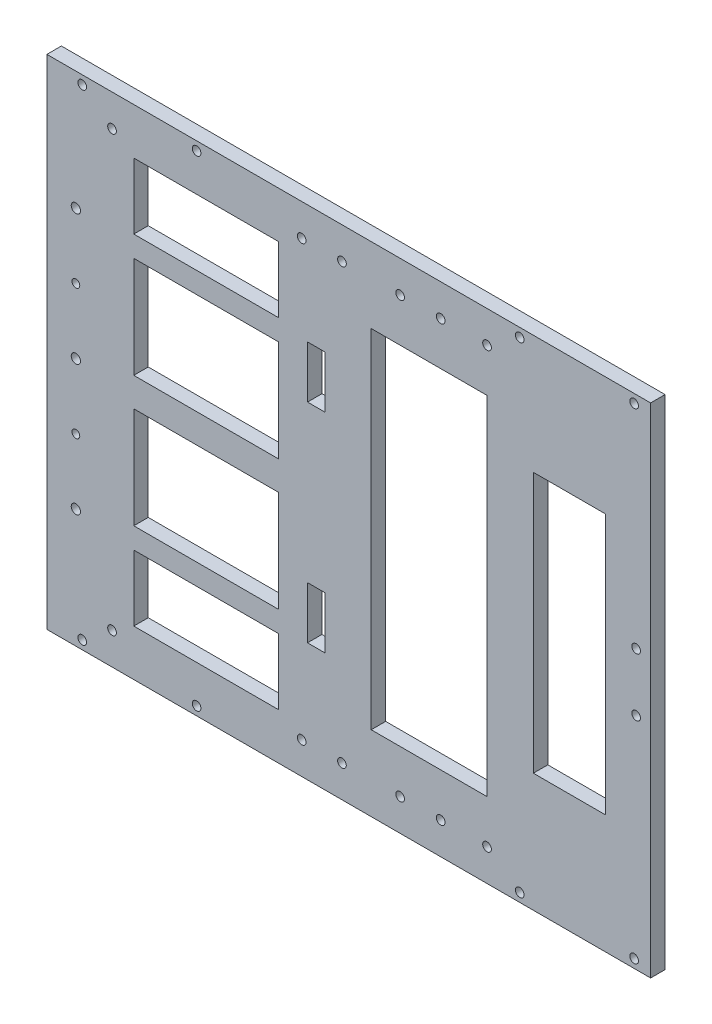
SolidWorks part; units mm, degrees
ref_plane "Front" through (0, 0, 0) normal (0, 0, 1) x (1, 0, 0)
ref_plane "Top" through (0, 0, 0) normal (0, 1, 0) x (1, 0, 0)
ref_plane "Right" through (0, 0, 0) normal (1, 0, 0) x (0, 0, -1)
sketch "草图1" plane through (0, 0, 0) normal (0, 0, 1) x (1, 0, 0)
  line L0 (-105.75, 86) -> (-105.75, 70)
  line L1 (-105.75, 86) -> (105.75, 86)
  line L2 (-105.75, 70) -> (-105.75, -86)
  line L3 (-105.75, -86) -> (105.75, -86)
  line L4 (105.75, 86) -> (105.75, -86)
  line L5 (-105.75, 86) -> (105.75, -86) construction
  line L6 (-105.75, -86) -> (105.75, 86) construction
  line L7 (-129.21, 0) -> (147.9998, 0) construction
  line L8 (-75.75, 70) -> (-25.75, 70)
  line L9 (-25.75, 70) -> (-25.75, 47.25)
  line L10 (-25.75, 47.25) -> (-75.75, 47.25)
  line L11 (-75.75, 47.25) -> (-75.75, 70)
  line L12 (-75.75, 40) -> (-25.75, 40)
  line L13 (-25.75, 40) -> (-25.75, 5)
  line L14 (-25.75, 5) -> (-75.75, 5)
  line L15 (-75.75, 5) -> (-75.75, 40)
  line L16 (-75.75, -70) -> (-25.75, -70)
  line L17 (6.25, 60) -> (46.25, 60)
  line L18 (6.25, 60) -> (6.25, -60)
  line L19 (6.25, -60) -> (46.25, -60)
  line L20 (46.25, -60) -> (46.25, 60)
  line L21 (62.25, 45) -> (87.25, 45)
  line L22 (87.25, 45) -> (87.25, -45)
  line L23 (87.25, -45) -> (62.25, -45)
  line L24 (62.25, -45) -> (62.25, 45)
  line L25 (-25.75, -5) -> (-75.75, -5)
  line L26 (-75.75, -40) -> (-25.75, -40)
  line L27 (-25.75, -40) -> (-25.75, -5)
  line L28 (-75.75, -5) -> (-75.75, -40)
  line L29 (-75.75, -47.25) -> (-75.75, -70)
  line L30 (-25.75, -70) -> (-25.75, -47.25)
  line L31 (-25.75, -47.25) -> (-75.75, -47.25)
  line L32 (-15.75, -27) -> (-9.75, -27)
  line L33 (-9.75, -45) -> (-9.75, -27)
  line L34 (-15.75, 45) -> (-9.75, 45)
  line L35 (-9.75, 45) -> (-9.75, 27)
  line L36 (-15.75, 45) -> (-15.75, 27)
  line L37 (-15.75, 27) -> (-9.75, 27)
  line L38 (-15.75, -45) -> (-15.75, -27)
  line L39 (-15.75, -45) -> (-9.75, -45)
  point P0 (0, 0)
extrude "凸台-拉伸1" add sketch "草图1" along normal blind 5
sketch "草图2" plane through (0, 0, 5) normal (0, 0, 1) x (1, 0, 0)
  line L0 (-171.9725, 0) -> (177.2997, 0) construction
  circle A0 centre (97.05, 83) radius 1.5
  circle A1 centre (-93.55, 83) radius 1.5
  circle A2 centre (57.55, 83) radius 1.5
  circle A3 centre (-54.05, 83) radius 1.5
  circle A4 centre (57.55, -83) radius 1.5
  circle A5 centre (97.05, -83) radius 1.5
  circle A6 centre (-54.05, -83) radius 1.5
  circle A7 centre (-93.55, -83) radius 1.5
extrude "切除-拉伸1" cut sketch "草图2" against normal blind 10
sketch "草图3" plane through (0, 0, 5) normal (0, 0, 1) x (1, 0, 0)
  line L2 (-189.9291, 0) -> (203.6358, 0) construction
  circle A0 centre (46.25, 75) radius 1.5
  circle A1 centre (46.25, -75) radius 1.5
  circle A2 centre (30.25, -75) radius 1.5
  circle A3 centre (30.25, 75) radius 1.5
  circle A4 centre (16.25, 75) radius 1.5
  circle A5 centre (16.25, -75) radius 1.5
extrude "切除-拉伸2" cut sketch "草图3" against normal blind 10
sketch "草图4" plane through (0, 0, 5) normal (0, 0, 1) x (1, 0, 0)
  line L0 (-148.2862, 0) -> (152.5464, 0) construction
  circle A0 centre (-3.85, 75) radius 1.5
  circle A1 centre (-3.85, -75) radius 1.5
extrude "切除-拉伸3" cut sketch "草图4" against normal blind 10
sketch "草图5" plane through (0, 0, 5) normal (0, 0, 1) x (1, 0, 0)
  circle A0 centre (-17.75, 75) radius 1.5
  circle A1 centre (-83.25, 75) radius 1.5
  circle A2 centre (-83.25, -75) radius 1.5
  circle A3 centre (-17.75, -75) radius 1.5
extrude "切除-拉伸4" cut sketch "草图5" against normal blind 24
sketch "草图6" plane through (0, 0, 5) normal (0, 0, 1) x (1, 0, 0)
  circle A0 centre (-95.75, 45) radius 1.6
  circle A1 centre (-95.75, 0) radius 1.6
  circle A2 centre (-95.75, -45) radius 1.6
extrude "切除-拉伸5" cut sketch "草图6" against normal blind 10
sketch "草图7" plane through (0, 0, 5) normal (0, 0, 1) x (1, 0, 0)
  line L0 (105.75, 86) -> (102.75, 86)
  line L1 (105.75, 86) -> (-105.75, 86) construction
  line L2 (102.75, 86) -> (102.75, -86)
  line L3 (-105.75, -86) -> (105.75, -86) construction
  line L4 (102.75, -86) -> (105.75, -86)
  line L5 (105.75, -86) -> (105.75, 86)
extrude "切除-拉伸6" cut sketch "草图7" against normal blind 10
sketch "草图9" plane through (0, 0, 5) normal (0, 0, 1) x (1, 0, 0)
  circle A0 centre (97.75, 10) radius 1.5
extrude "切除-拉伸7" cut sketch "草图9" against normal blind 5
mirror "镜向1" about plane through (0, 0, 0) normal (0, 1, 0) of "切除-拉伸7"
sketch "草图10" plane through (0, 0, 5) normal (0, 0, 1) x (1, 0, 0)
  circle A1 centre (-95.75, 22.5) radius 1.35
  circle A2 centre (-95.75, -22.5) radius 1.35
extrude "切除-拉伸8" cut sketch "草图10" against normal blind 10
